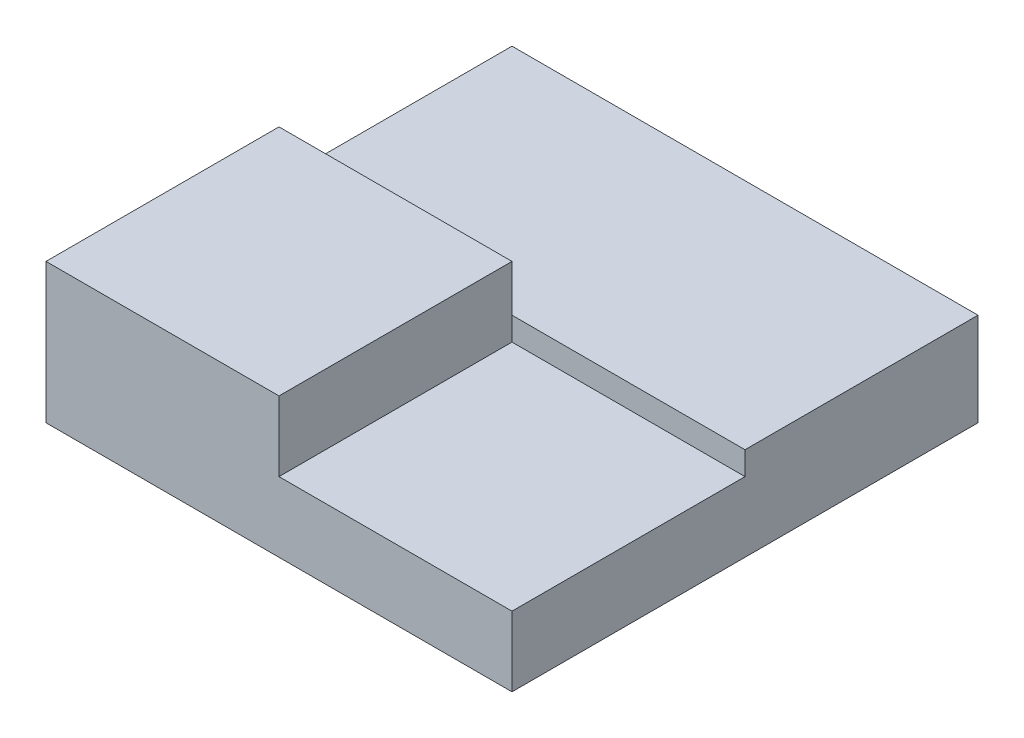
SolidWorks part; units mm, degrees
ref_plane "Front" through (0, 0, 0) normal (0, 0, 1) x (1, 0, 0)
ref_plane "Top" through (0, 0, 0) normal (0, 1, 0) x (1, 0, 0)
ref_plane "Right" through (0, 0, 0) normal (1, 0, 0) x (0, 0, -1)
sketch "Sketch1" plane through (0, 0, 0) normal (0, 1, 0) x (1, 0, 0)
  line L0 (0, 5.5461) -> (0, -3.2155) construction
  line L2 (-0.5, 0.5) -> (0.5, 0.5)
  line L3 (-0.5, 0.5) -> (-0.5, -0.5)
  line L4 (-0.5, -0.5) -> (0.5, -0.5)
  line L5 (-4.1375, 0) -> (5.7347, 0) construction
  line L6 (0.5, 0.5) -> (0.5, -0.5)
  point P9 (0, 0.5)
  point P10 (0.5, 0)
  dimension "D1" = 1
  dimension "D2" = 1
extrude "Boss-Extrude1" add sketch "Sketch1" along normal blind 0.3
sketch "Sketch2" plane through (0, 0.3, 0) normal (0, 1, 0) x (1, 0, 0)
  line L0 (0.5, -0.5) -> (0.5, 0.5) construction
  line L1 (-0.5, 0.5) -> (0.5, 0.5)
  line L2 (-0.5, 0.5) -> (-0.5, 0)
  line L3 (-0.5, 0) -> (0.5, 0)
  line L4 (0.5, 0.5) -> (0.5, 0)
extrude "Cut-Extrude1" cut sketch "Sketch2" against normal blind 0.1
sketch "Sketch4" plane through (0, 0.3, 0) normal (0, 1, 0) x (1, 0, 0)
  line L1 (0, 0) -> (0.5, 0)
  line L2 (0, 0) -> (0, -0.5)
  line L3 (0, -0.5) -> (0.5, -0.5)
  line L4 (0.5, 0) -> (0.5, -0.5)
extrude "Cut-Extrude2" cut sketch "Sketch4" against normal blind 0.15
sketch "Sketch5" plane through (0, 0, 0) normal (0, -1, 0) x (1, 0, 0)
  line L0 (-0.5, 0.5) -> (0.5, -0.5) construction
  point P4 (0, 0)
